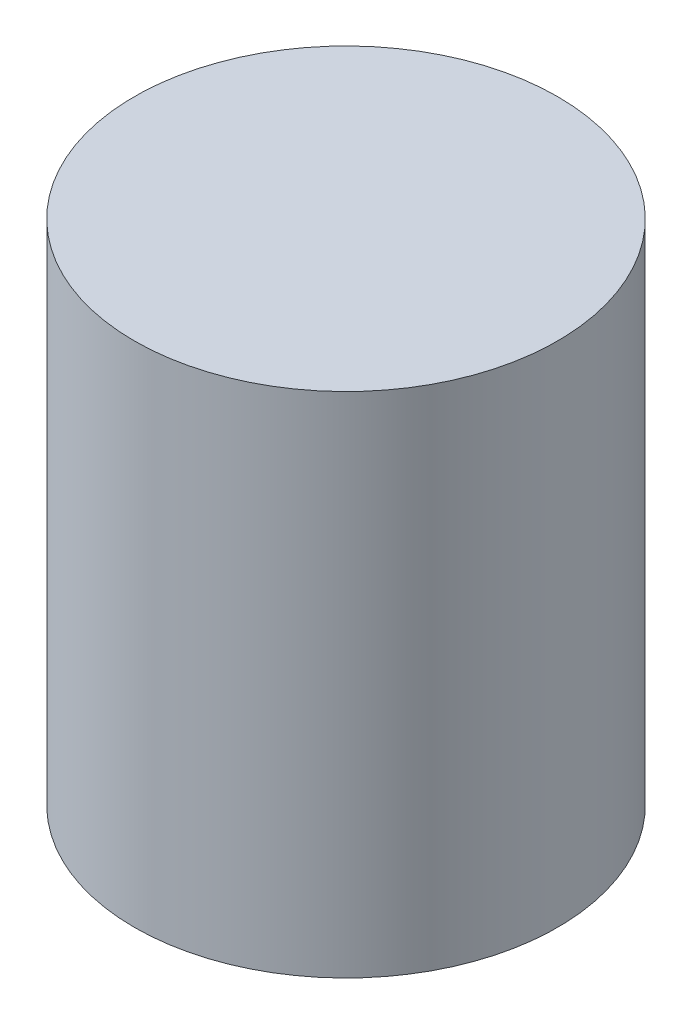
SolidWorks part; units mm, degrees
ref_plane "前视基准面" through (0, 0, 0) normal (0, 0, 1) x (1, 0, 0)
ref_plane "上视基准面" through (0, 0, 0) normal (0, 1, 0) x (1, 0, 0)
ref_plane "右视基准面" through (0, 0, 0) normal (1, 0, 0) x (0, 0, -1)
other "Configuration Table"
sketch "草图1" plane through (0, 0, 0) normal (0, 1, 0) x (1, 0, 0)
  circle A0 centre (0, 0) radius 25
  dimension "D1" = 50
extrude "凸台-拉伸1" add sketch "草图1" along normal blind 60
sketch "草图2" plane through (0, 0, 0) normal (0, -1, 0) x (1, 0, 0)
  circle A0 centre (0, 0) radius 22
  dimension "D1" = 44
extrude "切除-拉伸1" cut sketch "草图2" against normal blind 56
sketch "草图3" plane through (0, 0, 0) normal (0, -1, 0) x (1, 0, 0)
  circle A0 centre (0, 0) radius 22
  circle A1 centre (0, 0) radius 10
  dimension "D1" = 44
  dimension "D2" = 20
extrude "凸台-拉伸2" add sketch "草图3" against normal blind 4
